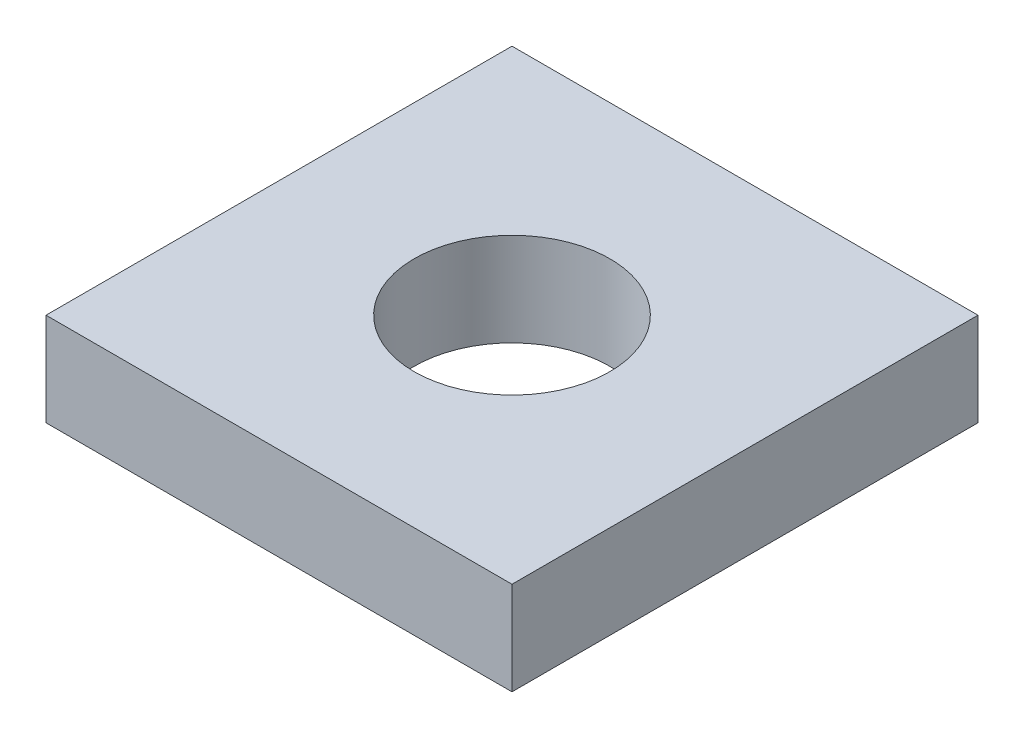
SolidWorks part; units mm, degrees
ref_plane "Front Plane" through (0, 0, 0) normal (0, 0, 1) x (1, 0, 0)
ref_plane "Top Plane" through (0, 0, 0) normal (0, 1, 0) x (1, 0, 0)
ref_plane "Right Plane" through (0, 0, 0) normal (1, 0, 0) x (0, 0, -1)
sketch "Sketch1" plane through (0, 0, 0) normal (0, 1, 0) x (1, 0, 0)
  line L0 (0, 10) -> (10, 0) construction
  line L1 (0, 0) -> (10, 0)
  line L2 (0, 0) -> (0, 10)
  line L3 (0, 10) -> (10, 10)
  line L4 (10, 0) -> (10, 10)
  line L5 (10, 10) -> (0, 0) construction
  circle A0 centre (5, 5) radius 2.1
  dimension "D3" = 4.2
  dimension "D1" = 10
  dimension "D2" = 10
extrude "Boss-Extrude1" add sketch "Sketch1" along normal blind 2
